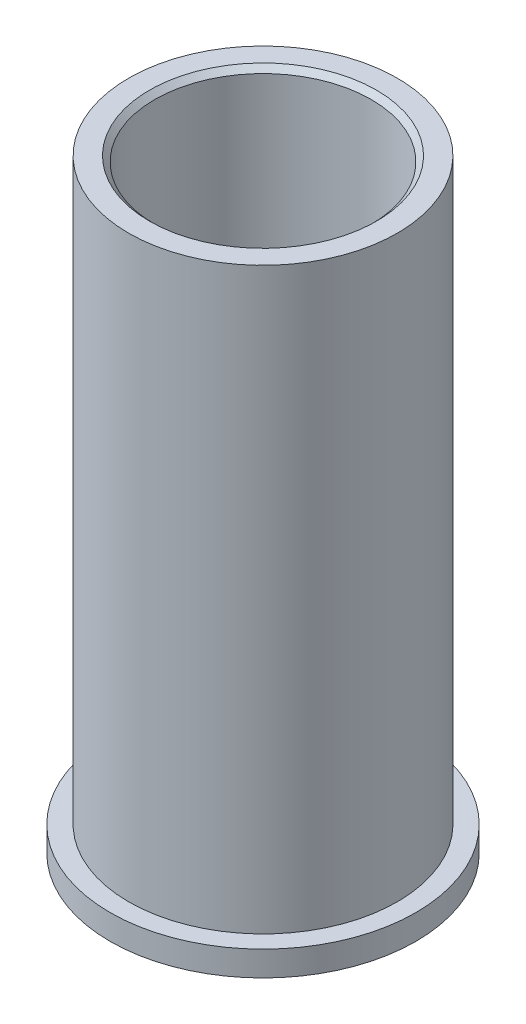
SolidWorks part; units mm, degrees
ref_plane "Front Plane" through (0, 0, 0) normal (0, 0, 1) x (1, 0, 0)
ref_plane "Top Plane" through (0, 0, 0) normal (0, 1, 0) x (1, 0, 0)
ref_plane "Right Plane" through (0, 0, 0) normal (1, 0, 0) x (0, 0, -1)
ref_plane "Plane1" through (0, 0, 0) normal (0, 0, -1) x (-1, 0, 0)
sketch "Sketch1" plane through (0, 0, 0) normal (0, 0, -1) x (-1, 0, 0)
  line L0 (-14.4526, 0) -> (-10.7315, 0)
  line L1 (-10.7315, 0) -> (-10.2235, 0.508)
  line L2 (-10.2235, 0.508) -> (-10.2235, 56.5912)
  line L3 (-10.2235, 56.5912) -> (-10.7315, 57.0992)
  line L4 (-10.7315, 57.0992) -> (-12.6962, 57.0992)
  line L5 (-12.6962, 57.0992) -> (-12.6962, 2.3622)
  line L6 (-12.6962, 2.3622) -> (-14.4526, 2.3622)
  line L7 (-14.4526, 2.3622) -> (-14.4526, 0)
  line L8 (0, 0) -> (0, 57.0992) construction
revolve "Revolve1" add sketch "Sketch1" angle 360 about L8
